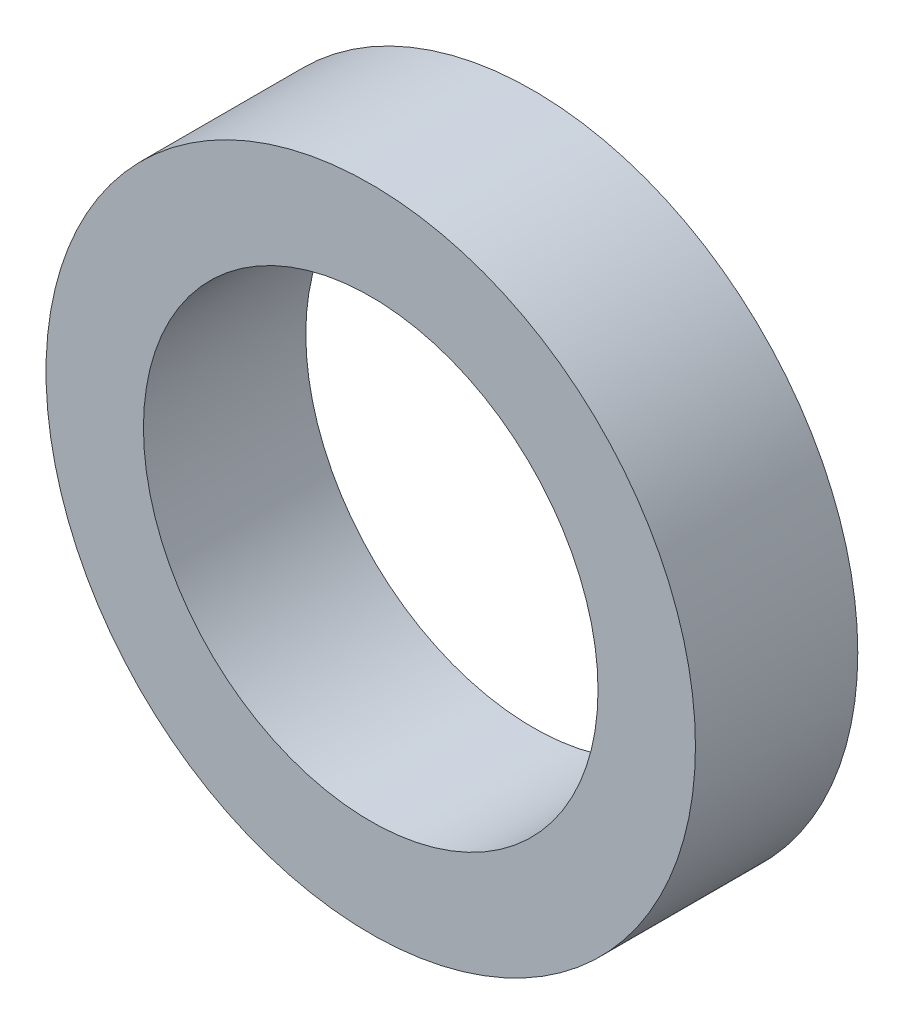
SolidWorks part; units mm, degrees
ref_plane "Front Plane" through (0, 0, 0) normal (0, 0, 1) x (1, 0, 0)
ref_plane "Top Plane" through (0, 0, 0) normal (0, 1, 0) x (1, 0, 0)
ref_plane "Right Plane" through (0, 0, 0) normal (1, 0, 0) x (0, 0, -1)
sketch "Sketch1" plane through (0, 0, 0) normal (0, 0, 1) x (1, 0, 0)
  circle A0 centre (0, 0) radius 7
  circle A1 centre (0, 0) radius 10
  dimension "D1" = 14
  dimension "D2" = 20
extrude "Boss-Extrude1" add sketch "Sketch1" along normal blind 5
